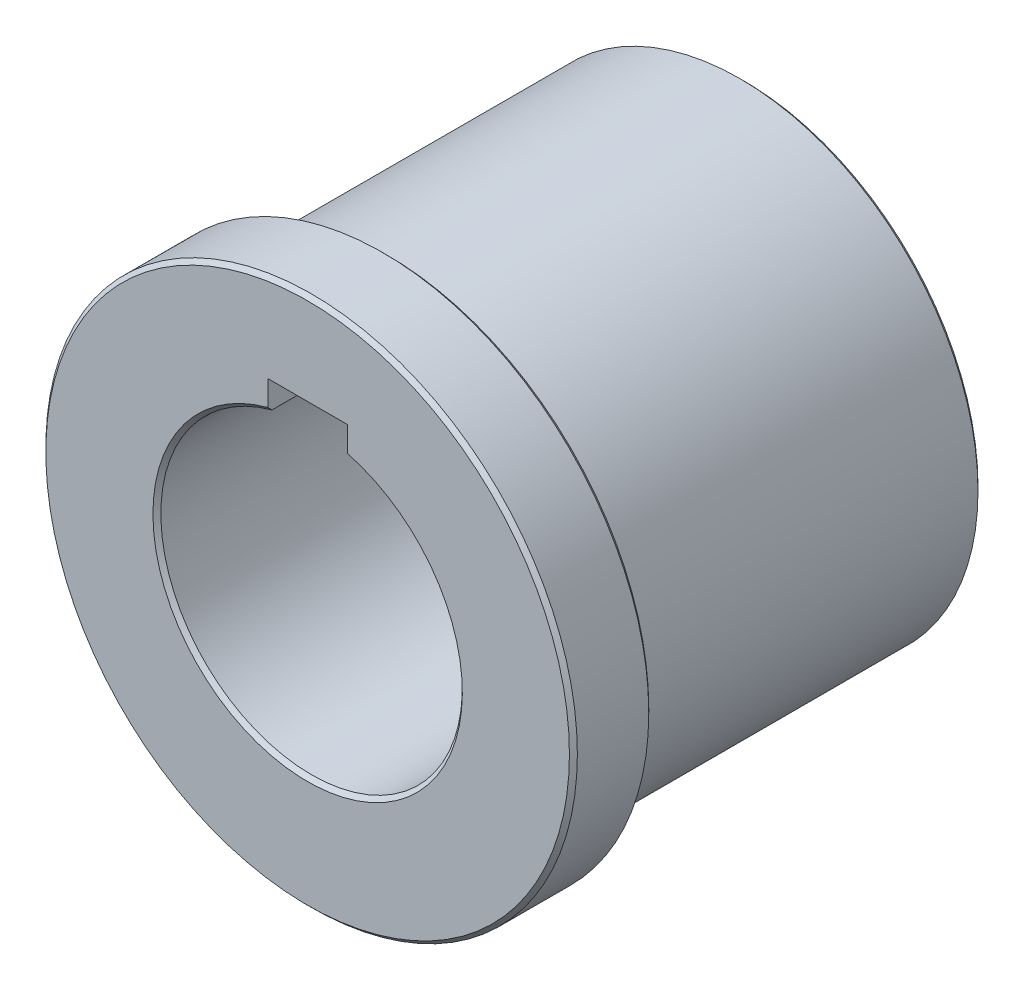
SolidWorks part; units mm, degrees
ref_plane "前视基准面" through (0, 0, 0) normal (0, 0, 1) x (1, 0, 0)
ref_plane "上视基准面" through (0, 0, 0) normal (0, 1, 0) x (1, 0, 0)
ref_plane "右视基准面" through (0, 0, 0) normal (1, 0, 0) x (0, 0, -1)
other "Configuration Table"
sketch "草图1" plane through (0, 0, 0) normal (0, 0, 1) x (1, 0, 0)
  circle A0 centre (0, 0) radius 30
  dimension "D1" = 60
extrude "凸台-拉伸1" add sketch "草图1" along normal blind 45
sketch "草图3" plane through (0, 0, 45) normal (0, 0, 1) x (1, 0, 0)
  circle A0 centre (0, 0) radius 33.5
  dimension "D1" = 67
extrude "凸台-拉伸2" add sketch "草图3" along normal blind 10
sketch "草图4" plane through (0, 0, 55) normal (0, 0, 1) x (1, 0, 0)
  line L0 (-33.5, 0) -> (33.5, 0) construction
  line L1 (0, 33.5) -> (0, -33.5) construction
  line L2 (-5, 18.3303) -> (-5, 22)
  line L3 (-5, 22) -> (5, 22)
  line L4 (5, 18.3303) -> (5, 22)
  circle A0 centre (0, 0) radius 33.5 construction
  arc A1 (-5, 18.3303) -> (5, 18.3303) centre (0, 0) ccw
  circle A2 centre (0, 0) radius 25 construction
  point P14 (0, 22)
  dimension "D1" = 41
  dimension "D2" = 19
  dimension "D4" = 50
  dimension "D3" = 10
extrude "切除-拉伸1" cut sketch "草图4" against normal through all
sketch "草图5" plane through (0, 0, 0) normal (0, 0, 1) x (1, 0, 0)
  line L0 (0, 0) -> (0, 33.5) construction
  circle A0 centre (0, 0) radius 25 construction
  circle A1 centre (0, 0) radius 33.5 construction
  circle A2 centre (-12.5, 21.6506) radius 3
  circle A3 centre (12.5, 21.6506) radius 3
  circle A4 centre (25, 0) radius 3
  circle A5 centre (12.5, -21.6506) radius 3
  circle A6 centre (-12.5, -21.6506) radius 3
  circle A7 centre (-25, 0) radius 3
  point P10 (12.5, 21.6506)
  point P11 (13.549, 21.0101)
  point P21 (0, 0)
  point P22 (0, 0)
  dimension "D1" = 50
  dimension "D2" = 6
  dimension "D3" = 30
  dimension "D4" = 6
extrude "切除-拉伸2" cut sketch "草图5" along normal blind 18
chamfer "倒角1" distance 0.5 angle 45 5 edges at (0, -19, 55) (0, -19, 0) (30, 0, 0) (33.5, 0, 45) (33.5, 0, 55)
